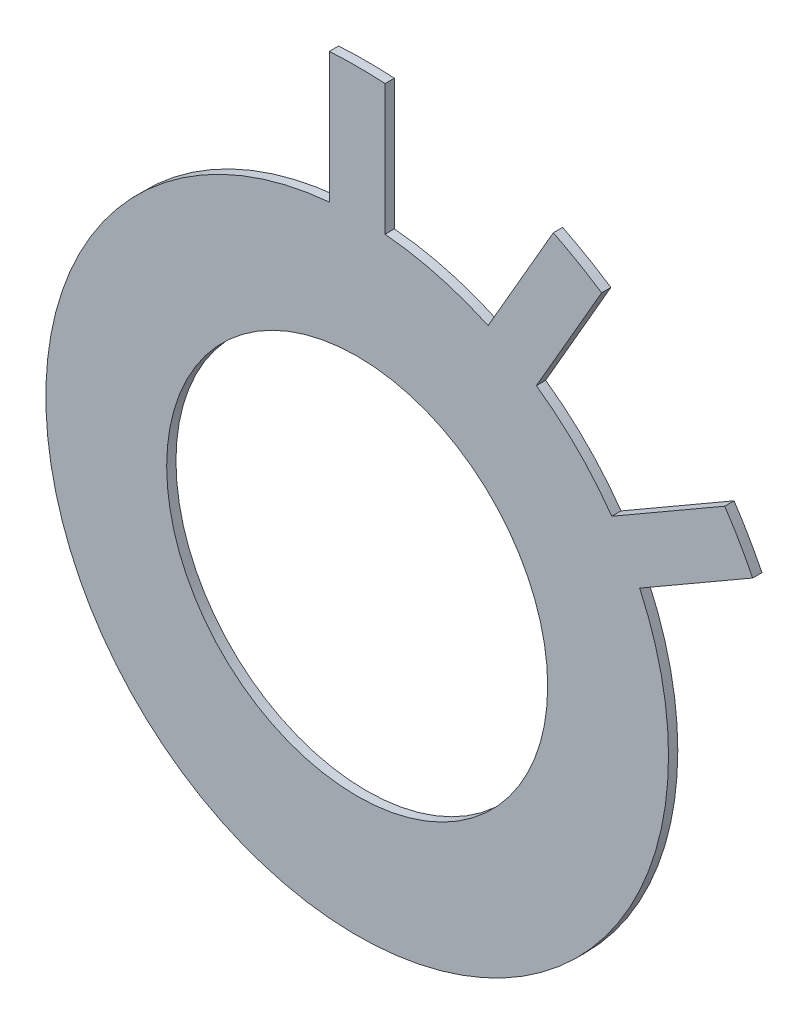
SolidWorks part; units mm, degrees
ref_plane "前视基准面" through (0, 0, 0) normal (0, 0, 1) x (1, 0, 0)
ref_plane "上视基准面" through (0, 0, 0) normal (0, 1, 0) x (1, 0, 0)
ref_plane "右视基准面" through (0, 0, 0) normal (1, 0, 0) x (0, 0, -1)
sketch "草图1" plane through (0, 0, 0) normal (0, 0, 1) x (1, 0, 0)
  line L0 (14.0846, 30.3953) -> (21.1045, 42.5541)
  line L2 (19.2808, 27.3953) -> (26.3007, 39.5541)
  line L3 (27.3953, 19.2808) -> (39.5541, 26.3007)
  line L4 (-3, 33.3654) -> (-3, 47.4052)
  line L5 (30.3953, 14.0846) -> (42.5541, 21.1045)
  line L8 (3, 33.3654) -> (3, 47.4052)
  arc A0 (-3, 33.3654) -> (30.3953, 14.0846) centre (0, 0) ccw
  circle A1 centre (0, 0) radius 20.5
  arc A2 (3, 47.4052) -> (-3, 47.4052) centre (0, 0) ccw
  arc A3 (26.3007, 39.5541) -> (21.1045, 42.5541) centre (0, 0) ccw
  arc A4 (42.5541, 21.1045) -> (39.5541, 26.3007) centre (0, 0) ccw
  arc A5 (14.0846, 30.3953) -> (3, 33.3654) centre (0, 0) ccw
  arc A6 (27.3953, 19.2808) -> (19.2808, 27.3953) centre (0, 0) ccw
  point P5 (-3, 0)
  point P7 (0, 53.4245)
  point P8 (-3, 53.4245)
  point P9 (3, 0)
  point P10 (3, 53.4245)
  dimension "D1" = 41
  dimension "D2" = 67
  dimension "D3" = 95
extrude "拉伸1" add sketch "草图1" along normal blind 1
